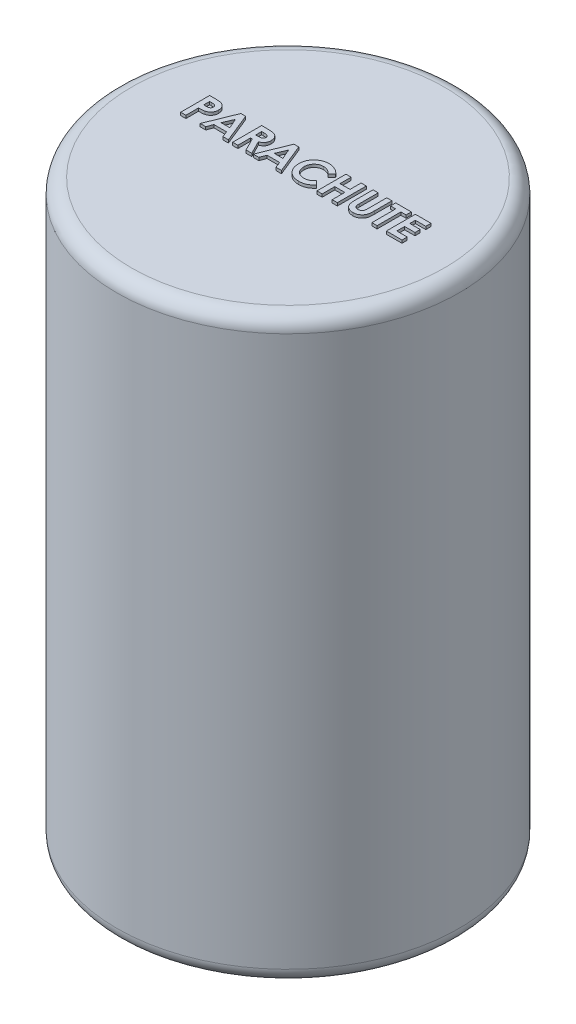
SolidWorks part; units mm, degrees
ref_plane "Front Plane" through (0, 0, 0) normal (0, 0, 1) x (1, 0, 0)
ref_plane "Top Plane" through (0, 0, 0) normal (0, 1, 0) x (1, 0, 0)
ref_plane "Right Plane" through (0, 0, 0) normal (1, 0, 0) x (0, 0, -1)
sketch "Sketch1" plane through (0, 0, 0) normal (0, 1, 0) x (1, 0, 0)
  circle A0 centre (0, 0) radius 75
  dimension "D1" = 150
extrude "Boss-Extrude1" add sketch "Sketch1" along normal blind 254
fillet "Fillet1" radius 6.35 2 edges at (0, 0, 75) (0, 254, 75)
sketch "Sketch2" plane through (0, 254, 0) normal (0, 1, 0) x (1, 0, 0)
  line L0 (65.3052, 0) -> (-65.3052, 0) construction
  text T0 "<b>PARACHUTE</b>" font "Century Gothic" height 12.7
  point P4 (0, 0)
extrude "Boss-Extrude2" add sketch "Sketch2" along normal blind 1.27
sketch "Sketch3" plane through (0, 0, 0) normal (0, 0, 1) x (1, 0, 0)
  line L0 (0, 0) -> (0, 251.3657) construction
  text T0 "<b>PARACHUTE</b>" font "Century Gothic" height 19.05
extrude "Cut-Extrude1" cut sketch "Sketch3" against normal mid plane 1.27
